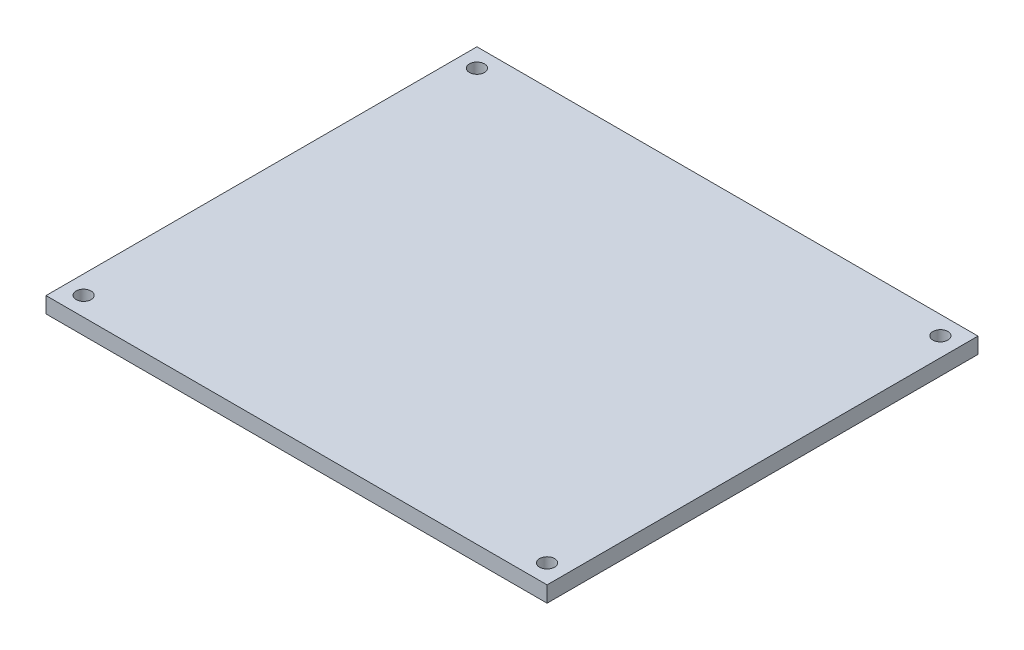
SolidWorks part; units mm, degrees
ref_plane "Front Plane" through (0, 0, 0) normal (0, 0, 1) x (1, 0, 0)
ref_plane "Top Plane" through (0, 0, 0) normal (0, 1, 0) x (1, 0, 0)
ref_plane "Right Plane" through (0, 0, 0) normal (1, 0, 0) x (0, 0, -1)
sketch "Sketch1" plane through (0, 0, 0) normal (0, 1, 0) x (1, 0, 0)
  line L1 (0, 0) -> (100, 0)
  line L2 (0, 0) -> (0, 86)
  line L3 (0, 86) -> (100, 86)
  line L4 (100, 0) -> (100, 86)
  circle A0 centre (3.7, 3.8) radius 1.5
  circle A1 centre (96.2, 3.8) radius 1.5
  circle A2 centre (3.7, 82.3) radius 1.5
  circle A3 centre (96.2, 82.3) radius 1.5
  dimension "D5" = 92.5
  dimension "D7" = 3
  dimension "D8" = 3
  dimension "D9" = 3
  dimension "D10" = 3
  dimension "D12" = 0
  dimension "D1" = 86
  dimension "D2" = 100
  dimension "D3" = 78.5
  dimension "D4" = 78.5
  dimension "D6" = 92.5
  dimension "D11" = 0
  dimension "D13" = 3.8
  dimension "D14" = 3.8
extrude "Boss-Extrude1" add sketch "Sketch1" along normal blind 3.175
